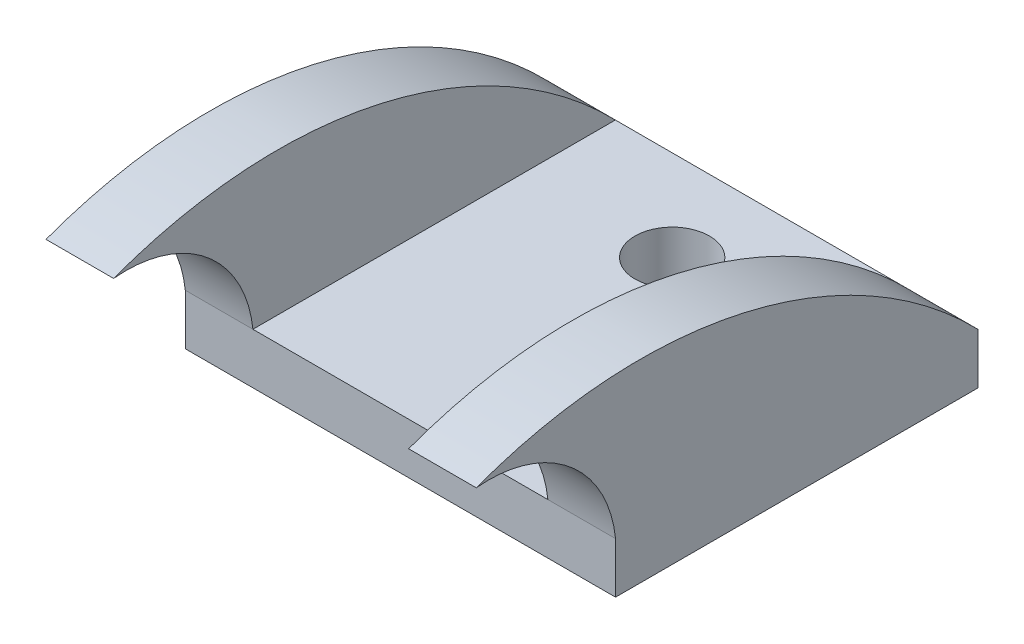
SolidWorks part; units mm, degrees
material "AISI 4340 Steel, annealed"
ref_plane "X-Y Datum" through (0, 0, 0) normal (0, 0, 1) x (1, 0, 0)
ref_plane "X-Z Datum" through (0, 0, 0) normal (0, 1, 0) x (1, 0, 0)
ref_plane "Y-Z Datum" through (0, 0, 0) normal (1, 0, 0) x (0, 0, -1)
sketch "Sketch1" plane through (0, 0, 0) normal (0, 1, 0) x (1, 0, 0)
  line L0 (20.2006, 32.3126) -> (20.2006, 15.2946) construction
  line L1 (0, 0) -> (40.4012, 0)
  line L2 (0, 0) -> (0, 34.036)
  line L3 (0, 34.036) -> (40.4012, 34.036)
  line L4 (40.4012, 0) -> (40.4012, 34.036)
  circle A0 centre (20.2006, 25.5224) radius 7.1006 construction
  circle A1 centre (20.2006, 25.5224) radius 1.2573
  dimension "D3" = 14.2011
  dimension "D4" = 8.5136
  dimension "D1" = 40.4012
  dimension "D2" = 34.036
extrude "Boss-Extrude1" add sketch "Sketch1" along normal blind 4.7625
hole_wizard "M6 Clearance Hole1" positions "Sketch3" profile "Sketch4" hole size "M6" standard "ANSI Metric" end condition through all
sketch "Sketch3" plane through (0, 4.7625, 0) normal (0, 1, 0) x (1, 0, 0)
  point P0 (20.2006, 25.5224)
sketch "Sketch4" plane through (20.2006, 4.7625, -25.5224) normal (1, 0, 0) x (0, 0, 1)
  line L0 (0, 0) -> (0, 4.7625)
  line L1 (0, 4.7625) -> (3.5, 4.7625)
  line L2 (3.5, 4.7625) -> (3.5, 0)
  line L5 (3.5, 0) -> (0, 0)
  line L11 (0, -6.35) -> (0, 107.95) construction
  dimension "Thru Hole Dia." = 7
  dimension "Thru Hole Depth" = 4.7625
sketch "Sketch5" plane through (40.4012, 0, 0) normal (1, 0, 0) x (0, 0, -1)
  line L2 (0, 4.7625) -> (34.036, 4.7625)
  arc A2 (-13.0789, 15.4355) -> (0, 4.7625) centre (-11.9246, 3.4999) cw
  arc A3 (-13.0789, 15.4355) -> (34.036, 4.7625) centre (2.291, -26.0444) cw
extrude "Boss-Extrude3" add sketch "Sketch5" against normal blind 6.35
ref_plane "Plane1" through (20.2006, 0, 0) normal (1, 0, 0) x (0, 0, -1)
mirror "Mirror1" about plane through (20.2006, 0, 0) normal (1, 0, 0) of "Boss-Extrude3"
